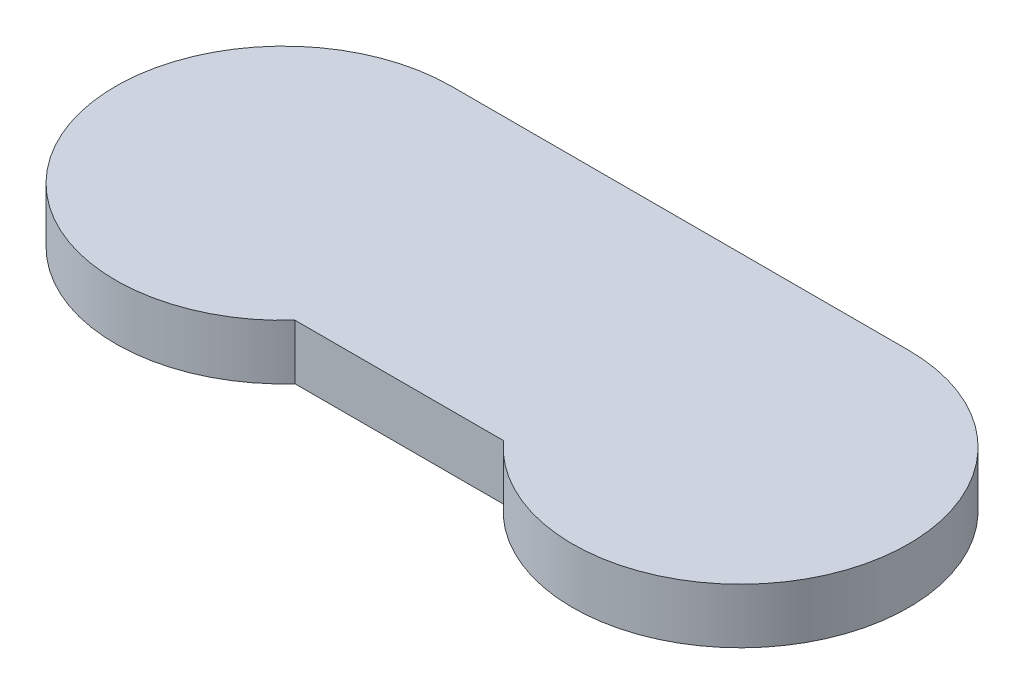
SolidWorks part; units mm, degrees
ref_plane "Front Plane" through (0, 0, 0) normal (0, 0, 1) x (1, 0, 0)
ref_plane "Top Plane" through (0, 0, 0) normal (0, 1, 0) x (1, 0, 0)
ref_plane "Right Plane" through (0, 0, 0) normal (1, 0, 0) x (0, 0, -1)
sketch "Sketch1" plane through (0, 0, 0) normal (0, 1, 0) x (1, 0, 0)
  line L1 (72, -30.5) -> (-72, -30.5) construction
  line L3 (41.5, 30.5) -> (-41.5, 30.5)
  line L5 (72, -30.5) -> (-72, 30.5) construction
  line L6 (72, 30.5) -> (-11.3836, -4.8222) construction
  line L7 (-18.9168, -20.5) -> (18.9168, -20.5)
  line L8 (-58.9884, -24.9881) -> (-72, -30.5) construction
  arc A0 (-41.5, 30.5) -> (-18.9168, -20.5) centre (-41.5, 0) ccw
  arc A1 (18.9168, -20.5) -> (41.5, 30.5) centre (41.5, 0) ccw
  point P0 (0, 0)
  dimension "D4" = 61
  dimension "D2" = 83
  dimension "D1" = 144
  dimension "D3" = 61
  dimension "D6" = 10
extrude "Boss-Extrude1" add sketch "Sketch1" along normal blind 10
sketch "Sketch2" plane through (0, 0, 0) normal (0, 1, 0) x (1, 0, 0)
  line L6 (41.5, 25.5) -> (-41.5, 25.5)
  line L7 (-21.2515, -15.5) -> (21.2515, -15.5)
  line L8 (41.5, 25.5) -> (-41.5, 25.5)
  line L9 (-21.2515, -15.5) -> (21.2515, -15.5)
  arc A8 (21.2515, -15.5) -> (41.5, 25.5) centre (41.5, 0) ccw
  arc A9 (-41.5, 25.5) -> (-21.2515, -15.5) centre (-41.5, 0) ccw
  arc A10 (21.2515, -15.5) -> (41.5, 25.5) centre (41.5, 0) ccw
  arc A11 (-41.5, 25.5) -> (-21.2515, -15.5) centre (-41.5, 0) ccw
  dimension "D1" = 5
extrude "Cut-Extrude1" cut sketch "Sketch2" along normal blind 5
